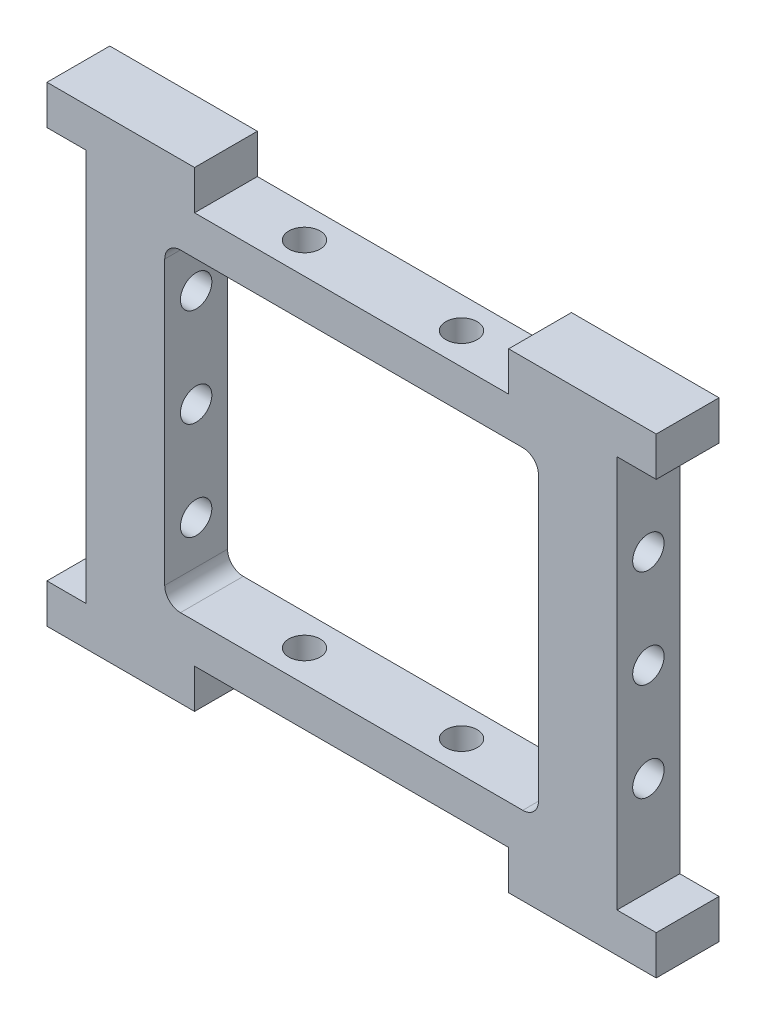
SolidWorks part; units mm, degrees
ref_plane "前视基准面" through (0, 0, 0) normal (0, 0, 1) x (1, 0, 0)
ref_plane "上视基准面" through (0, 0, 0) normal (0, 1, 0) x (1, 0, 0)
ref_plane "右视基准面" through (0, 0, 0) normal (1, 0, 0) x (0, 0, -1)
sketch "草图1" plane through (0, 0, 0) normal (0, 0, 1) x (1, 0, 0)
  line L1 (0, 0) -> (67.6, 0)
  line L2 (0, 0) -> (0, 50)
  line L3 (0, 50) -> (67.6, 50)
  line L4 (67.6, 0) -> (67.6, 50)
  dimension "D1" = 50
  dimension "D2" = 67.6
extrude "凸台-拉伸1" add sketch "草图1" along normal blind 8
sketch "草图2" plane through (0, 0, 0) normal (-1, 0, 0) x (0, 0, 1)
  line L0 (8, 50) -> (8, 0) construction
  line L1 (8, 0) -> (0, 0) construction
  line L2 (8, 50) -> (0, 50) construction
  circle A0 centre (4, 37.5) radius 2
  circle A2 centre (4, 25) radius 2
  circle A3 centre (4, 12.5) radius 2
  dimension "D1" = 4
  dimension "D2" = 12.5
  dimension "D3" = 4
  dimension "D4" = 4
  dimension "D5" = 4
  dimension "D8" = 4
  dimension "D9" = 12.5
  dimension "D6" = 12.5
extrude "切除-拉伸1" cut sketch "草图2" against normal blind 10
ref_plane "基准面1" through (33.8, 0, 0) normal (1, 0, 0) x (0, 0, -1)
mirror "镜向1" about plane through (33.8, 0, 0) normal (1, 0, 0) of "切除-拉伸1"
sketch "草图3" plane through (0, 50, 0) normal (0, 1, 0) x (1, 0, 0)
  line L0 (0, -8) -> (0, 0) construction
  line L1 (67.6, -8) -> (0, -8) construction
  circle A0 centre (23.8, -4) radius 2
  circle A1 centre (43.8, -4) radius 2
  dimension "D1" = 4
  dimension "D2" = 4
  dimension "D5" = 4
  dimension "D3" = 20
  dimension "D4" = 23.8
extrude "切除-拉伸2" cut sketch "草图3" against normal blind 10
ref_plane "基准面2" through (0, 25, 0) normal (0, 1, 0) x (1, 0, 0)
mirror "镜向2" about plane through (0, 25, 0) normal (0, 1, 0) of "切除-拉伸2"
sketch "草图4" plane through (0, 0, 0) normal (0, 0, -1) x (-1, 0, 0)
  line L0 (-67.6, 50) -> (0, 50) construction
  line L1 (-53.8, 50) -> (-72.6, 50)
  line L2 (-53.8, 50) -> (-53.8, 55)
  line L3 (-53.8, 55) -> (-72.6, 55)
  line L4 (-72.6, 50) -> (-72.6, 55)
  line L5 (0, 0) -> (-67.6, 0) construction
  line L6 (-53.8, 0) -> (-72.6, 0)
  line L7 (-53.8, 0) -> (-53.8, -5)
  line L8 (-53.8, -5) -> (-72.6, -5)
  line L9 (-72.6, 0) -> (-72.6, -5)
  line L10 (-67.6, 0) -> (-67.6, 50) construction
  line L11 (-13.8, 0) -> (5, 0)
  line L12 (-13.8, 0) -> (-13.8, -5)
  line L13 (-13.8, -5) -> (5, -5)
  line L14 (5, 0) -> (5, -5)
  line L15 (-13.8, 50) -> (5, 50)
  line L16 (-13.8, 50) -> (-13.8, 55)
  line L17 (-13.8, 55) -> (5, 55)
  line L18 (5, 50) -> (5, 55)
  line L19 (0, 50) -> (0, 0) construction
  point P24 (-53.8, 52.5)
  dimension "D1" = 5
  dimension "D2" = 5
  dimension "D3" = 5
  dimension "D4" = 5
  dimension "D5" = 5
  dimension "D6" = 5
  dimension "D7" = 5
  dimension "D8" = 5
  dimension "D9" = 40
  dimension "D10" = 40
  dimension "D11" = 13.8
  dimension "D12" = 13.8
extrude "凸台-拉伸2" add sketch "草图4" against normal blind 8
sketch "草图5" plane through (0, 0, 0) normal (0, 0, -1) x (-1, 0, 0)
  line L0 (-67.6, 0) -> (-67.6, 50) construction
  line L1 (-57.6, 45) -> (-10, 45)
  line L2 (-57.6, 45) -> (-57.6, 5)
  line L3 (-57.6, 5) -> (-10, 5)
  line L4 (-10, 45) -> (-10, 5)
  line L5 (-53.8, 50) -> (-13.8, 50) construction
  dimension "D1" = 47.6
  dimension "D2" = 10
  dimension "D3" = 40
  dimension "D4" = 5
extrude "切除-拉伸3" cut sketch "草图5" against normal blind 8
fillet "圆角1" radius 2 4 edges at (10, 45, 4) (10, 5, 4) (57.6, 5, 4) (57.6, 45, 4)
